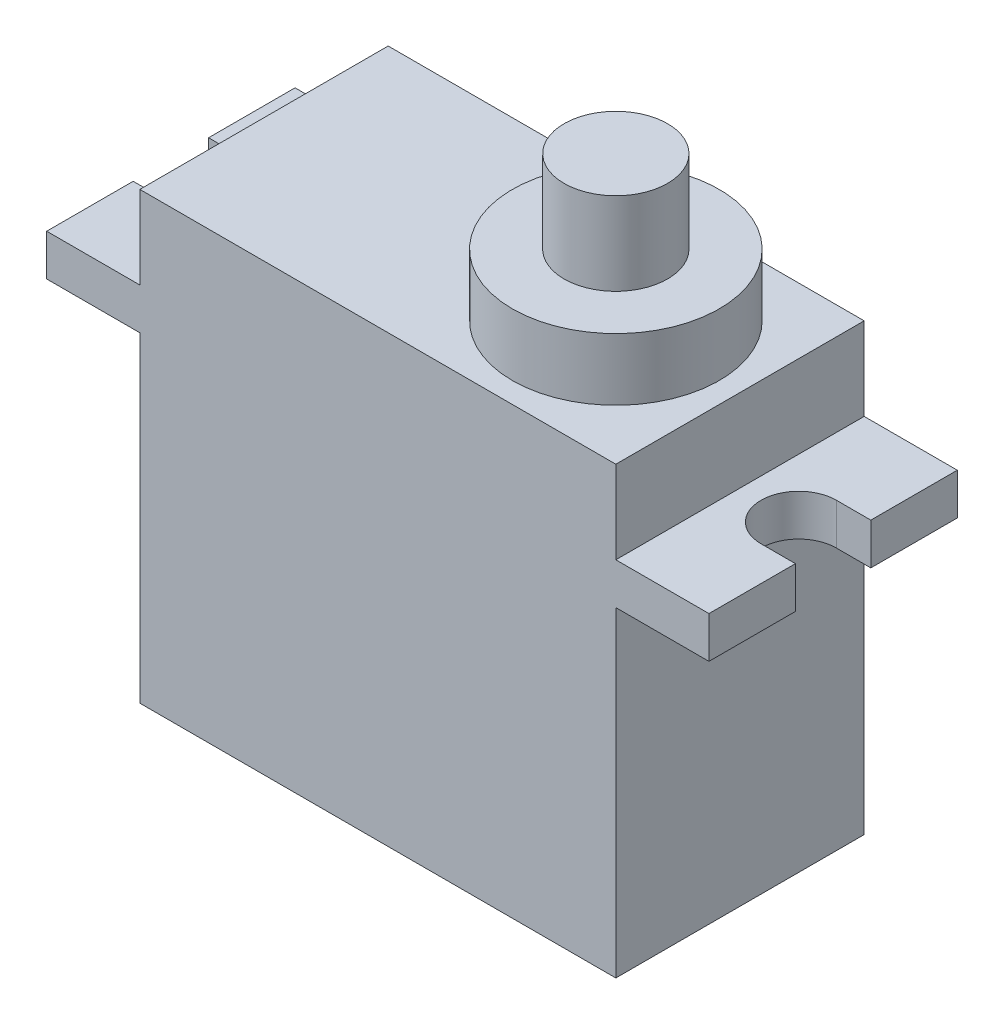
SolidWorks part; units mm, degrees
material "6061-T6 (SS)"
ref_plane "Front Plane" through (0, 0, 0) normal (0, 0, 1) x (1, 0, 0)
ref_plane "Top Plane" through (0, 0, 0) normal (0, 1, 0) x (1, 0, 0)
ref_plane "Right Plane" through (0, 0, 0) normal (1, 0, 0) x (0, 0, -1)
sketch "Sketch1" plane through (0, 0, 0) normal (0, 0, 1) x (1, 0, 0)
  line L1 (-11.5, 10.75) -> (11.5, 10.75)
  line L2 (-11.5, 10.75) -> (-11.5, -10.75)
  line L3 (-11.5, -10.75) -> (11.5, -10.75)
  line L4 (11.5, 10.75) -> (11.5, -10.75)
  line L5 (-11.5, 10.75) -> (11.5, -10.75) construction
  line L6 (-11.5, -10.75) -> (11.5, 10.75) construction
  point P0 (0, 0)
  dimension "D1" = 21.5
  dimension "D2" = 23
extrude "Boss-Extrude1" add sketch "Sketch1" along normal blind 12
ref_plane "Plane1" through (0, 6.75, 0) normal (0, 1, 0) x (1, 0, 0)
sketch "Sketch4" plane through (0, 6.75, 0) normal (0, 1, 0) x (1, 0, 0)
  line L1 (-16, 0) -> (16, 0)
  line L2 (-16, 0) -> (-16, -12)
  line L3 (-16, -12) -> (16, -12)
  line L4 (16, 0) -> (16, -12)
  line L5 (-16, 0) -> (16, -12) construction
  line L6 (-16, -12) -> (16, 0) construction
  point P0 (0, -6)
  dimension "D1" = 32
extrude "Boss-Extrude2" add sketch "Sketch4" against normal blind 2
sketch "Sketch5" plane through (0, 10.75, 0) normal (0, 1, 0) x (1, 0, 0)
  line L0 (11.5, 0) -> (-11.5, 0) construction
  line L1 (11.5, -12) -> (11.5, 0) construction
  circle A0 centre (5.5, -6) radius 5
  dimension "D1" = 10
  dimension "D2" = 6
  dimension "D3" = 6
extrude "Boss-Extrude3" add sketch "Sketch5" along normal blind 3
sketch "Sketch6" plane through (0, 13.75, 0) normal (0, 1, 0) x (1, 0, 0)
  circle A0 centre (5.5, -6) radius 2.5
  dimension "D1" = 5
extrude "Boss-Extrude4" add sketch "Sketch6" along normal blind 4
sketch "Sketch7" plane through (0, 6.75, 0) normal (0, 1, 0) x (1, 0, 0)
  line L0 (-16, -6) -> (-14.3376, -6) construction
  line L1 (-16, 0) -> (-16, -12) construction
  line L2 (-16, -4.1787) -> (-14.3376, -4.1787)
  line L3 (-16, -7.8213) -> (-14.3376, -7.8213)
  line L4 (0, -6.6) -> (0, 6.6) construction
  line L5 (16, -6) -> (14.3376, -6) construction
  line L6 (16, -4.1787) -> (14.3376, -4.1787)
  line L7 (16, -7.8213) -> (14.3376, -7.8213)
  arc A0 (-16, -4.1787) -> (-16, -7.8213) centre (-16, -6) ccw
  arc A1 (-14.3376, -7.8213) -> (-14.3376, -4.1787) centre (-14.3376, -6) ccw
  arc A2 (16, -4.1787) -> (16, -7.8213) centre (16, -6) cw
  arc A3 (14.3376, -7.8213) -> (14.3376, -4.1787) centre (14.3376, -6) cw
  point P4 (-15.1688, -6)
  point P13 (15.1688, -6)
extrude "Cut-Extrude1" cut sketch "Sketch7" against normal blind 4
